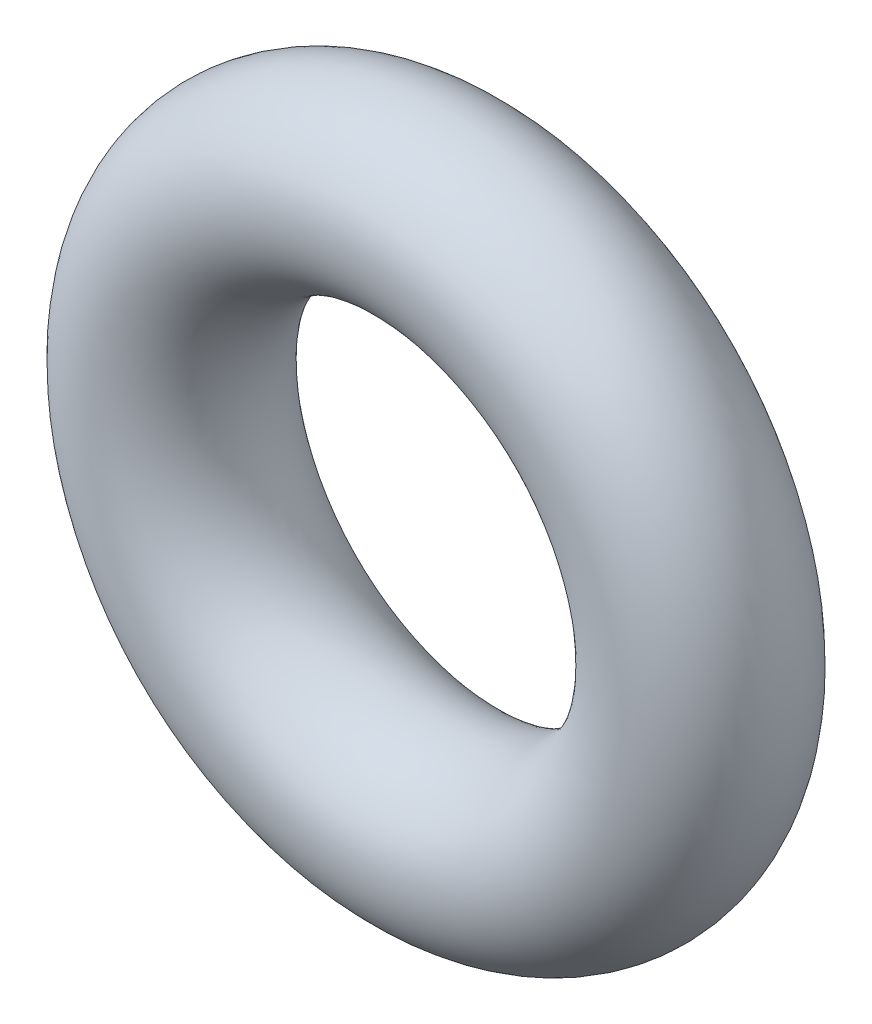
SolidWorks part; units mm, degrees
ref_plane "Front Plane" through (0, 0, 0) normal (0, 0, 1) x (1, 0, 0)
ref_plane "Top Plane" through (0, 0, 0) normal (0, 1, 0) x (1, 0, 0)
ref_plane "Right Plane" through (0, 0, 0) normal (1, 0, 0) x (0, 0, -1)
sketch "Sketch1" plane through (0, 0, 0) normal (0, 1, 0) x (1, 0, 0)
  line L0 (0, 0) -> (-10, 0) construction
  line L1 (0, 5) -> (0, 0) construction
  circle A0 centre (-7.5, 0) radius 2.5
  dimension "D1" = 5
  dimension "D2" = 10
  dimension "D3" = 5
revolve "Revolve1" add sketch "Sketch1" angle 360 about L1
